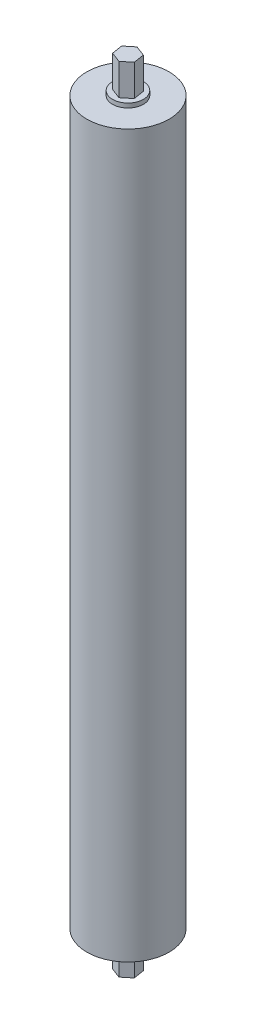
SolidWorks part; units mm, degrees
ref_plane "Front Plane" through (0, 0, 0) normal (0, 0, 1) x (1, 0, 0)
ref_plane "Top Plane" through (0, 0, 0) normal (0, 1, 0) x (1, 0, 0)
ref_plane "Right Plane" through (0, 0, 0) normal (1, 0, 0) x (0, 0, -1)
sketch "Sketch1" plane through (0, 0, 0) normal (0, 1, 0) x (1, 0, 0)
  circle A0 centre (0, 0) radius 24.0411
  dimension "D1" = 48.0822
extrude "Boss-Extrude1" add sketch "Sketch1" along normal blind 211.0105
sketch "Sketch2" plane through (0, 211.0105, 0) normal (0, 1, 0) x (1, 0, 0)
  circle A0 centre (0, 0) radius 9.017
  dimension "D1" = 18.034
extrude "Boss-Extrude2" add sketch "Sketch2" along normal blind 2.54
sketch "Sketch3" plane through (0, 213.5505, 0) normal (0, 1, 0) x (1, 0, 0)
  line L1 (5.9637, -2.2645) -> (4.943, 4.0324)
  line L2 (4.943, 4.0324) -> (-1.0207, 6.297)
  line L3 (-1.0207, 6.297) -> (-5.9637, 2.2645)
  line L4 (-5.9637, 2.2645) -> (-4.943, -4.0324)
  line L5 (-4.943, -4.0324) -> (1.0207, -6.297)
  line L6 (1.0207, -6.297) -> (5.9637, -2.2645)
  circle A0 centre (0, 0) radius 5.5245 construction
  dimension "D1" = 11.049
extrude "Boss-Extrude3" add sketch "Sketch3" along normal blind 18.415
mirror "Mirror1" about plane through (0, 0, 0) normal (0, 1, 0) of "Boss-Extrude2", "Boss-Extrude3", "Boss-Extrude1"
